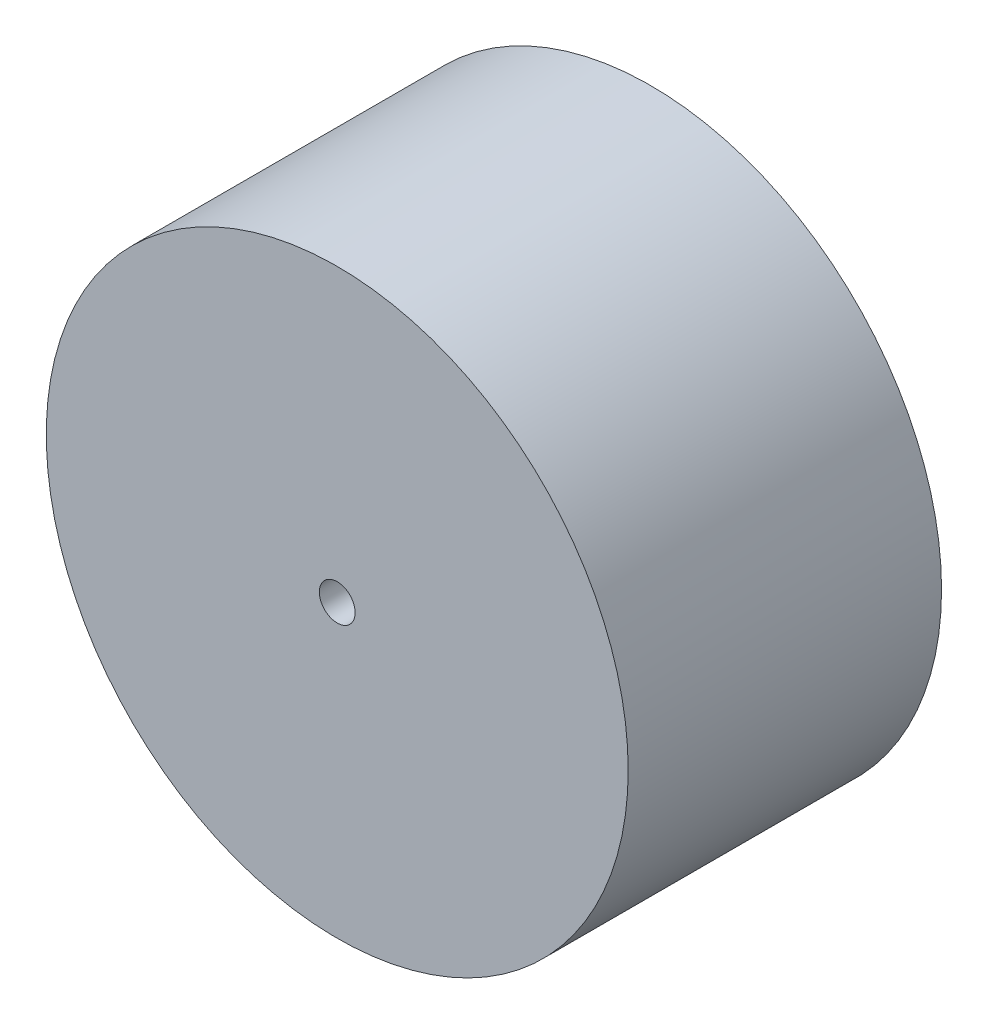
SolidWorks part; units mm, degrees
material "ABS"
ref_plane "Front" through (0, 0, 0) normal (0, 0, 1) x (1, 0, 0)
ref_plane "Top" through (0, 0, 0) normal (0, 1, 0) x (1, 0, 0)
ref_plane "Right" through (0, 0, 0) normal (1, 0, 0) x (0, 0, -1)
sketch "Sketch1" plane through (0, 0, 0) normal (0, 0, 1) x (1, 0, 0)
  circle A0 centre (0, 0) radius 32.5
  circle A1 centre (0, 0) radius 2
  dimension "D1" = 65
  dimension "D2" = 4
extrude "Boss-Extrude1" add sketch "Sketch1" along normal blind 35
